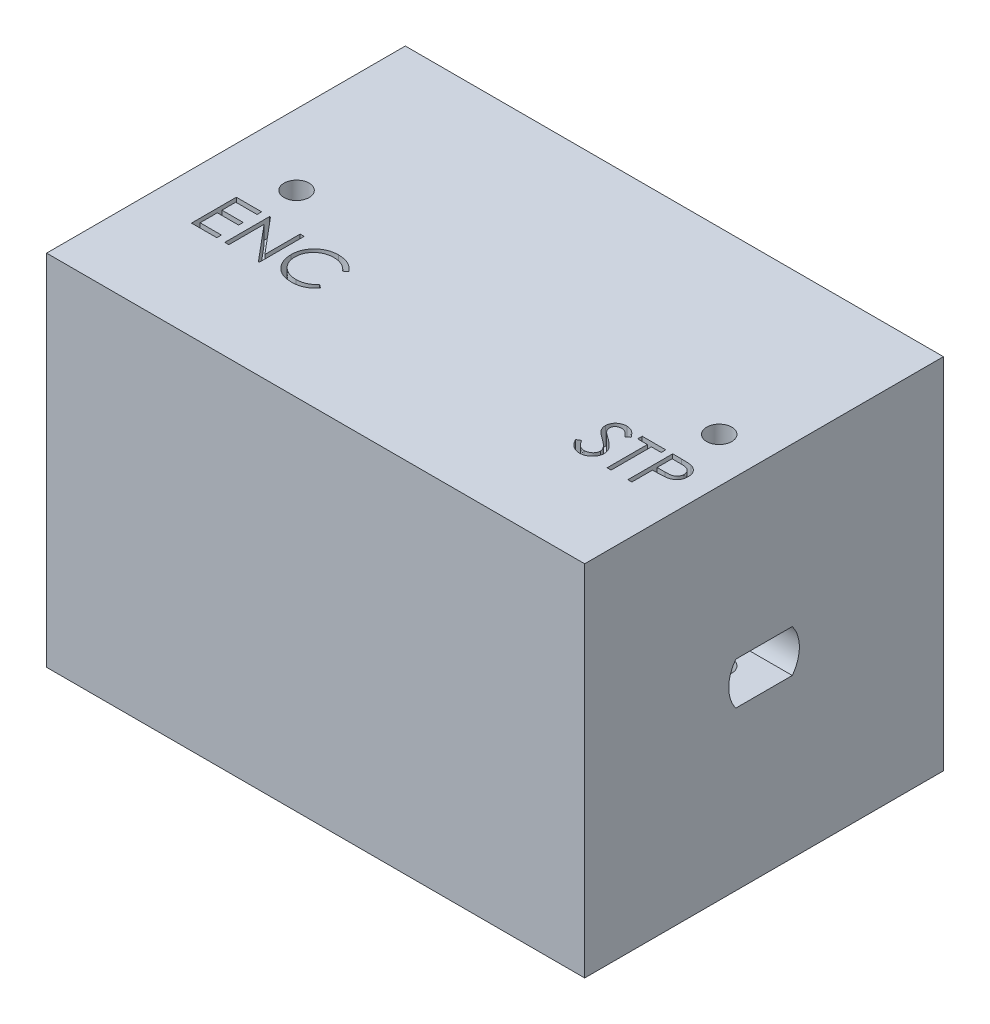
SolidWorks part; units mm, degrees
ref_plane "Front Plane" through (0, 0, 0) normal (0, 0, 1) x (1, 0, 0)
ref_plane "Top Plane" through (0, 0, 0) normal (0, 1, 0) x (1, 0, 0)
ref_plane "Right Plane" through (0, 0, 0) normal (1, 0, 0) x (0, 0, -1)
sketch "Sketch1" plane through (0, 0, 0) normal (1, 0, 0) x (0, 0, -1)
  line L1 (-6.4508, 15.119) -> (18.9492, 15.119)
  line L2 (-6.4508, 15.119) -> (-6.4508, -10.281)
  line L3 (-6.4508, -10.281) -> (18.9492, -10.281)
  line L4 (18.9492, 15.119) -> (18.9492, -10.281)
  circle A0 centre (6.2492, 2.419) radius 1.5
  dimension "D3" = 3
  dimension "D1" = 25.4
  dimension "D2" = 25.4
extrude "Boss-Extrude1" add sketch "Sketch1" along normal blind 38.1
sketch "Sketch4" plane through (0, 15.119, 0) normal (0, 1, 0) x (1, 0, 0)
  text T0 "STP"
sketch "Sketch5" plane through (0, 15.119, 0) normal (0, 1, 0) x (1, 0, 0)
  text T0 "ENC"
extrude "Cut-Extrude2" cut sketch "Sketch5" against normal blind 1.27
extrude "Cut-Extrude3" cut sketch "Sketch4" against normal blind 1.27
sketch "Sketch6" plane through (0, 0, 0) normal (-1, 0, 0) x (0, 0, 1)
  line L3 (-8.8473, 3.919) -> (-3.6511, 3.919)
  arc A0 (-8.8473, 3.919) -> (-3.6511, 3.919) centre (-6.2492, 2.419) ccw
  dimension "D1" = 6
extrude "Cut-Extrude4" cut sketch "Sketch6" against normal blind 19.05
sketch "Sketch7" plane through (38.1, 0, 0) normal (1, 0, 0) x (0, 0, -1)
  line L0 (4.2492, 0.919) -> (8.2492, 0.919)
  line L3 (4.2492, 3.919) -> (8.2492, 3.919)
  arc A0 (8.2492, 0.919) -> (8.2492, 3.919) centre (6.2492, 2.419) ccw
  arc A1 (4.2492, 3.919) -> (4.2492, 0.919) centre (6.2492, 2.419) ccw
extrude "Cut-Extrude5" cut sketch "Sketch7" against normal blind 19.05
sketch "Sketch2" plane through (0, 15.119, 0) normal (0, 1, 0) x (1, 0, 0)
  line L0 (0, 18.9492) -> (0, -6.4508) construction
  line L1 (38.1, 18.9492) -> (38.1, -6.4508) construction
  circle A0 centre (5, 6.2492) radius 0.889
  circle A1 centre (34.925, 6.2492) radius 0.889
  point P8 (38.1, 6.2492)
  point P9 (0, 6.2492)
  dimension "D1" = 5
  dimension "D2" = 3.175
  dimension "D3" = 0
  dimension "D4" = 0
extrude "Cut-Extrude6" cut sketch "Sketch2" against normal blind 25.4
